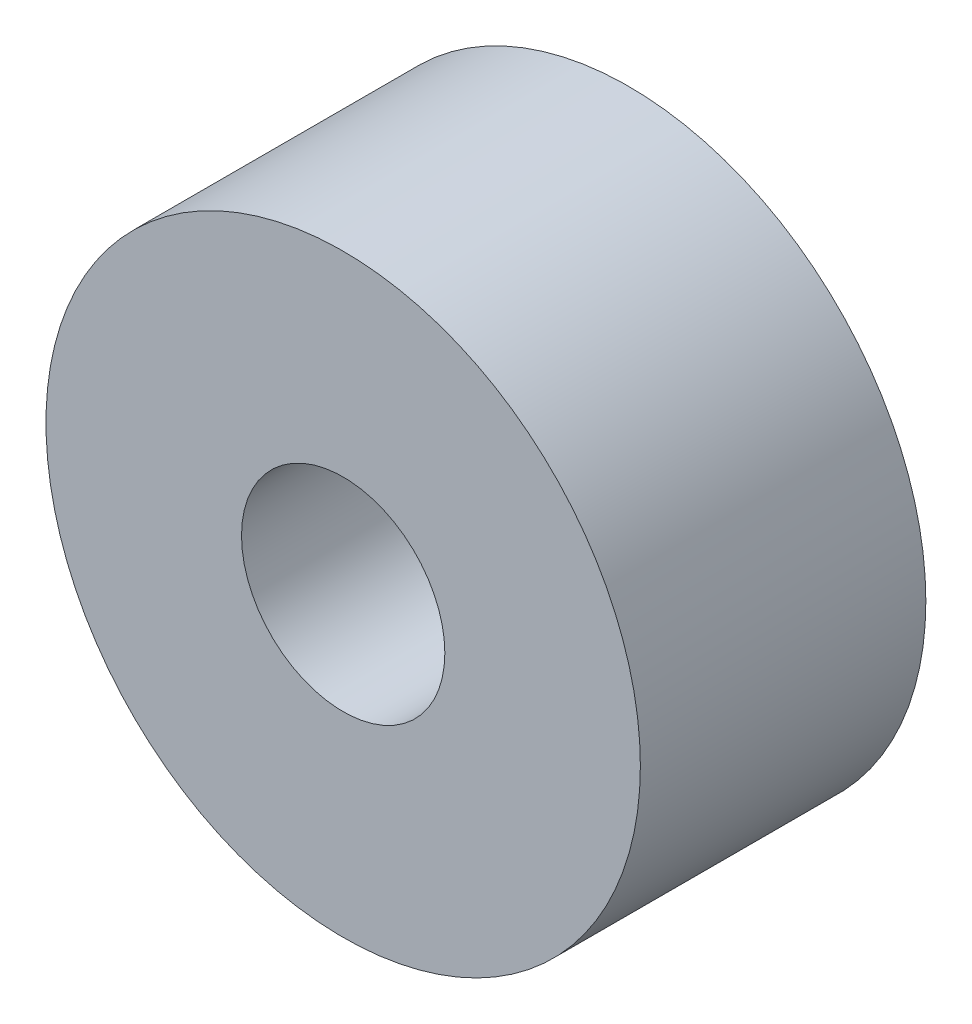
SolidWorks part; units mm, degrees
ref_plane "Front Plane" through (0, 0, 0) normal (0, 0, 1) x (1, 0, 0)
ref_plane "Top Plane" through (0, 0, 0) normal (0, 1, 0) x (1, 0, 0)
ref_plane "Right Plane" through (0, 0, 0) normal (1, 0, 0) x (0, 0, -1)
sketch "Sketch1" plane through (0, 0, 0) normal (0, 0, 1) x (1, 0, 0)
  circle A0 centre (0, 0) radius 3.302
  circle A1 centre (0, 0) radius 9.652
  dimension "D1" = 6.604
  dimension "D2" = 6.35
extrude "Boss-Extrude1" add sketch "Sketch1" along normal blind 9.271
